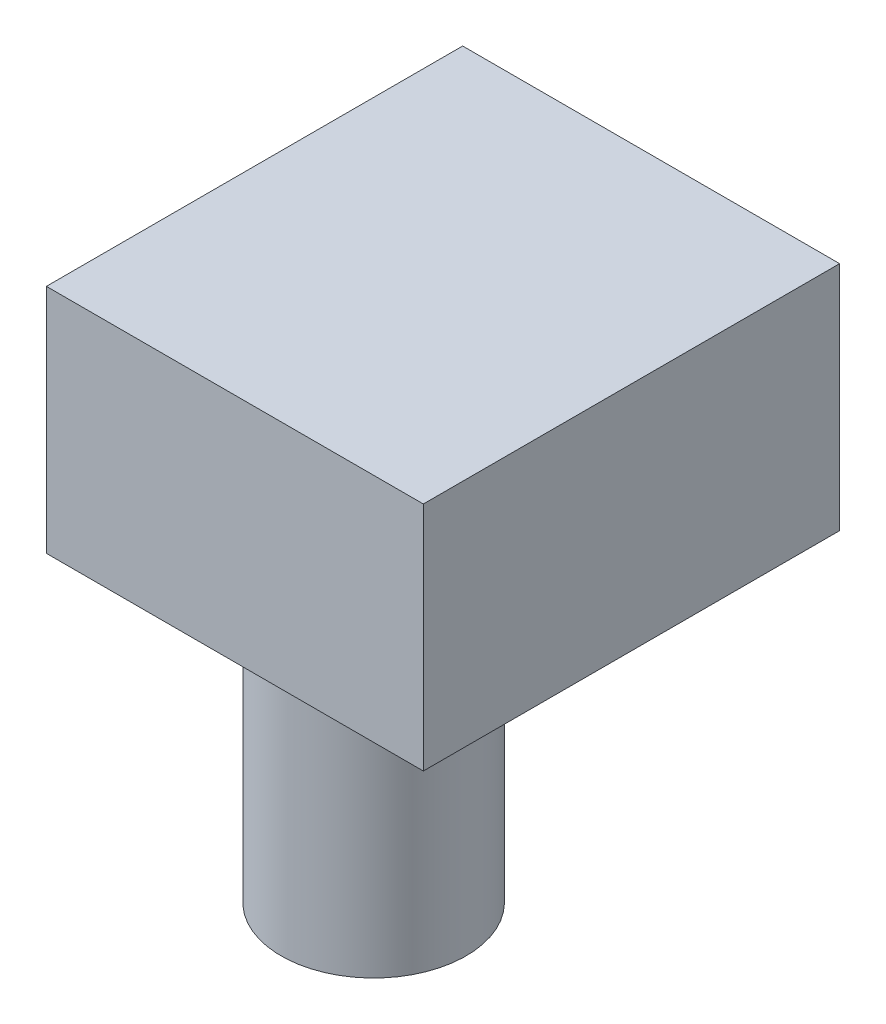
SolidWorks part; units mm, degrees
material "1060-H16"
ref_plane "Спереди" through (0, 0, 0) normal (0, 0, 1) x (1, 0, 0)
ref_plane "Сверху" through (0, 0, 0) normal (0, 1, 0) x (1, 0, 0)
ref_plane "Справа" through (0, 0, 0) normal (1, 0, 0) x (0, 0, -1)
sketch "Эскиз1" plane through (0, 0, 0) normal (0, 1, 0) x (1, 0, 0)
  line L1 (0, 0) -> (16.3, 0)
  line L2 (0, 0) -> (0, 18)
  line L3 (0, 18) -> (16.3, 18)
  line L4 (16.3, 0) -> (16.3, 18)
  dimension "D1" = 16.3
  dimension "D2" = 18
extrude "Бобышка-Вытянуть1" add sketch "Эскиз1" along normal blind 10
sketch "Эскиз3" plane through (0, 0, 0) normal (0, -1, 0) x (1, 0, 0)
  line L1 (0, 0) -> (16.3, 0) construction
  line L2 (8.15, -18) -> (8.15, 0) construction
  line L3 (16.3, -18) -> (0, -18) construction
  line L4 (0, 0) -> (16.3, 0) construction
  circle A0 centre (8.15, -6) radius 4
  point P4 (8.15, 0)
  dimension "D3" = 8
  dimension "D2" = 6
extrude "Бобышка-Вытянуть2" add sketch "Эскиз3" along normal blind 12
